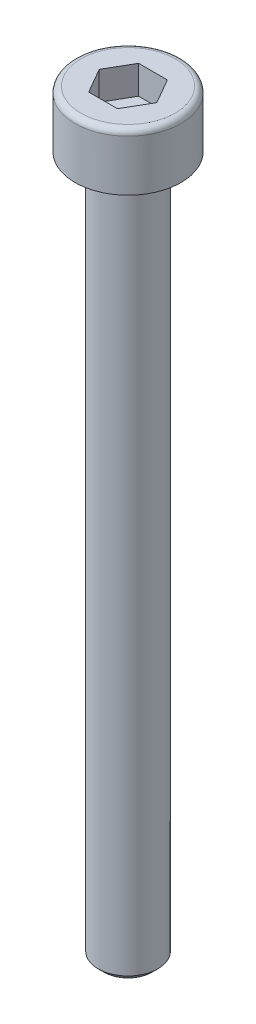
SolidWorks part; units mm, degrees
material "Cast Stainless Steel"
ref_plane "Front Plane" through (0, 0, 0) normal (0, 0, 1) x (1, 0, 0)
ref_plane "Top Plane" through (0, 0, 0) normal (0, 1, 0) x (1, 0, 0)
ref_plane "Right Plane" through (0, 0, 0) normal (1, 0, 0) x (0, 0, -1)
sketch "Sketch1" plane through (0, 0, 0) normal (0, 0, 1) x (1, 0, 0)
  line L0 (0, 0) -> (0, 2.86)
  line L1 (0, 2.86) -> (2.66, 2.86)
  line L2 (2.66, 2.86) -> (2.66, 0)
  line L3 (2.66, 0) -> (1.5, 0)
  line L4 (1.5, 0) -> (1.5, -35)
  line L5 (1.5, -35) -> (0, -35)
  line L6 (0, -35) -> (0, 0)
  line L7 (0, 2.86) -> (0, 12.7536) construction
  dimension "D1" = 35
  dimension "D2" = 2.86
  dimension "D3" = 3
  dimension "D4" = 5.32
revolve "Revolve1" add sketch "Sketch1" angle 360 about L7
chamfer "Chamfer1" distance 0.3 angle 45 1 edges at (0, -35, -1.5)
fillet "Fillet1" radius 0.3 1 edges at (0, 2.86, -2.66)
sketch "Sketch2" plane through (0, 2.86, 0) normal (0, 1, 0) x (1, 0, 0)
  line L1 (0.7217, -1.25) -> (1.4434, 0)
  line L2 (1.4434, 0) -> (0.7217, 1.25)
  line L3 (0.7217, 1.25) -> (-0.7217, 1.25)
  line L4 (-0.7217, 1.25) -> (-1.4434, 0)
  line L5 (-1.4434, 0) -> (-0.7217, -1.25)
  line L6 (-0.7217, -1.25) -> (0.7217, -1.25)
  circle A0 centre (0, 0) radius 1.25 construction
  dimension "D1" = 2.5
extrude "Cut-Extrude1" cut sketch "Sketch2" against normal blind 1.43
equation "\"d\"= 3"
equation "\"dk\"= 5.32"
equation "\"k\"= 2.86"
equation "\"s\"= 2.5"
equation "\"L\"= 35"
equation "\"D4@Sketch1\"=\"dk\""
equation "\"D2@Sketch1\"=\"k\""
equation "\"D1@Sketch1\"=\"L\""
equation "\"D3@Sketch1\"=\"d\""
equation "\"D1@Chamfer1\"=\"d\"/10"
equation "\"D1@Fillet1\"=\"d\"/10"
equation "\"D1@Sketch2\"=\"s\""
equation "\"D1@Cut-Extrude1\"=\"k\"/2"
